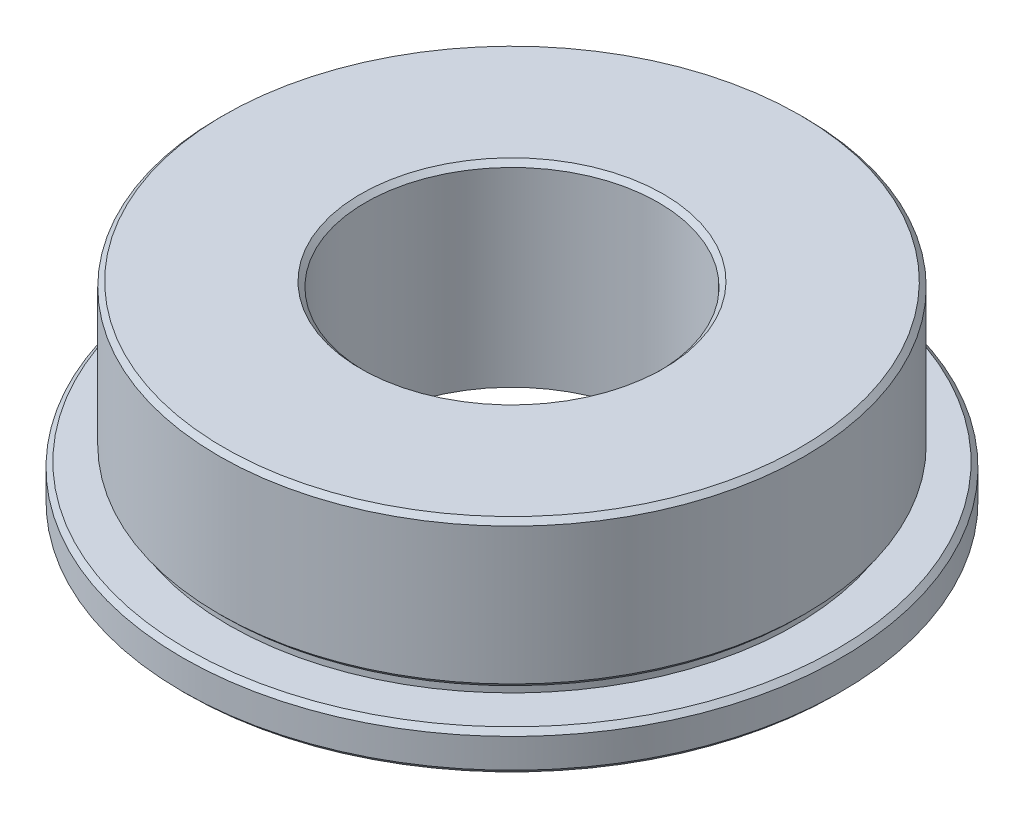
SolidWorks part; units mm, degrees
material "AISI Type 316L stainless steel"
ref_plane "前视基准面" through (0, 0, 0) normal (0, 0, 1) x (1, 0, 0)
ref_plane "上视基准面" through (0, 0, 0) normal (0, 1, 0) x (1, 0, 0)
ref_plane "右视基准面" through (0, 0, 0) normal (1, 0, 0) x (0, 0, -1)
other "Configuration Table"
sketch "草图2" plane through (0, 0, 0) normal (0, 0, 1) x (1, 0, 0)
  line L0 (0, 0) -> (3, 0) construction
  line L1 (3, 0) -> (3, 4) construction
  line L2 (3, 4) -> (0, 4) construction
  line L3 (0, 4) -> (0, 0) construction
  line L4 (3, 4) -> (3, 0)
  line L5 (3, 0) -> (6.75, 0)
  line L6 (6.75, 0) -> (6.75, 0.8)
  line L7 (6.75, 0.8) -> (5.8, 0.8)
  line L8 (5.8, 0.8) -> (5.8, 1)
  line L9 (5.8, 1) -> (6, 1)
  line L10 (6, 1) -> (6, 4)
  line L11 (6, 4) -> (3, 4)
  dimension "D1" = 4
  dimension "D2" = 6
  dimension "D3" = 12
  dimension "D4" = 0.2
  dimension "D5" = 0.8
  dimension "D6" = 13.5
revolve "旋转1" add sketch "草图2" angle 360 about L3
chamfer "倒角2" distance 0.1 angle 45 5 edges at (0, 4, 3) (0, 1, 6) (0, 0.8, 6.75) (0, 0, 6.75) (0, 4, 6)
